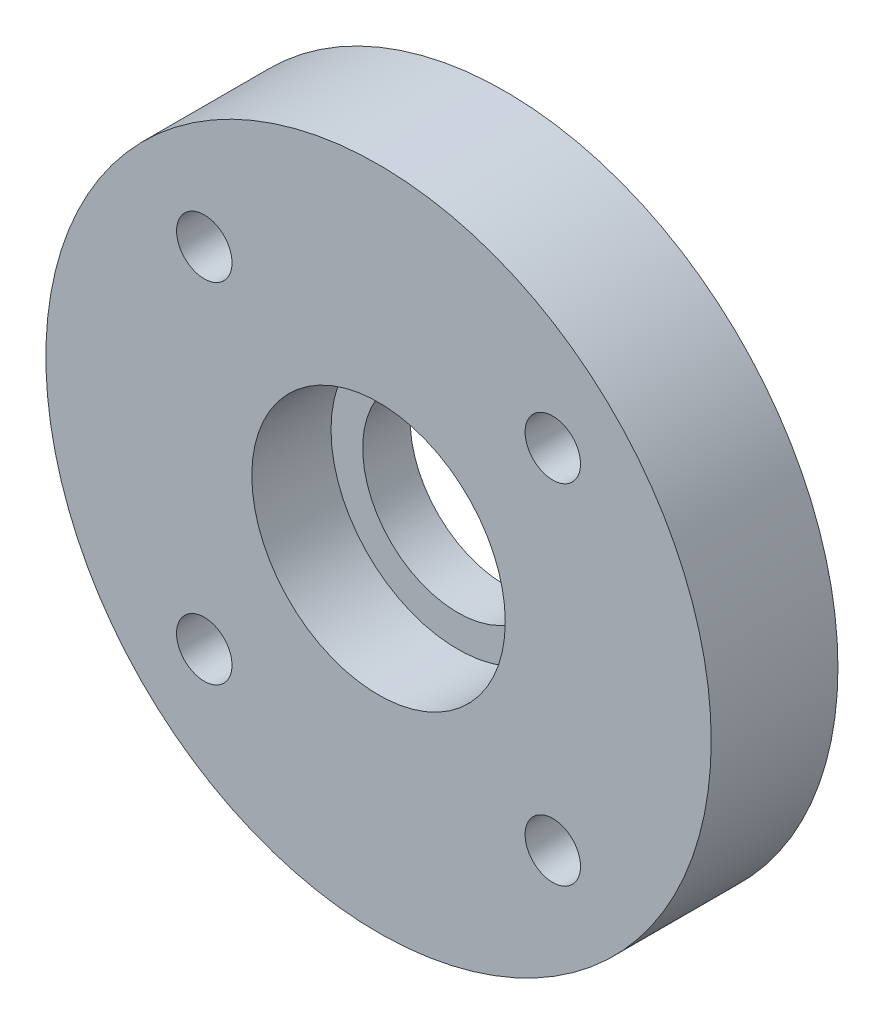
SolidWorks part; units mm, degrees
ref_plane "Front Plane" through (0, 0, 0) normal (0, 0, 1) x (1, 0, 0)
ref_plane "Top Plane" through (0, 0, 0) normal (0, 1, 0) x (1, 0, 0)
ref_plane "Right Plane" through (0, 0, 0) normal (1, 0, 0) x (0, 0, -1)
sketch "Sketch1" plane through (0, 0, 0) normal (0, 0, 1) x (1, 0, 0)
  circle A0 centre (0, 0) radius 21
  dimension "D1" = 42
extrude "Boss-Extrude1" add sketch "Sketch1" along normal blind 8
sketch "Sketch2" plane through (0, 0, 8) normal (0, 0, 1) x (1, 0, 0)
  circle A0 centre (0, 0) radius 6
  dimension "D1" = 12
extrude "Cut-Extrude1" cut sketch "Sketch2" against normal through all
sketch "Sketch3" plane through (0, 0, 8) normal (0, 0, 1) x (1, 0, 0)
  circle A0 centre (0, 0) radius 8
  dimension "D1" = 16
extrude "Cut-Extrude2" cut sketch "Sketch3" against normal blind 5
sketch "Sketch4" plane through (0, 0, 8) normal (0, 0, 1) x (1, 0, 0)
  line L0 (-2.5357, 0) -> (0, 0) construction
  line L1 (0, 0) -> (0, 3.4289) construction
  circle A0 centre (-11, 11) radius 1.75
  circle A2 centre (11, 11) radius 1.75
  circle A3 centre (11, -11) radius 1.75
  circle A4 centre (-11, -11) radius 1.75
  dimension "D1" = 3.5
  dimension "D2" = 11
  dimension "D3" = 11
extrude "Cut-Extrude3" cut sketch "Sketch4" against normal through all
